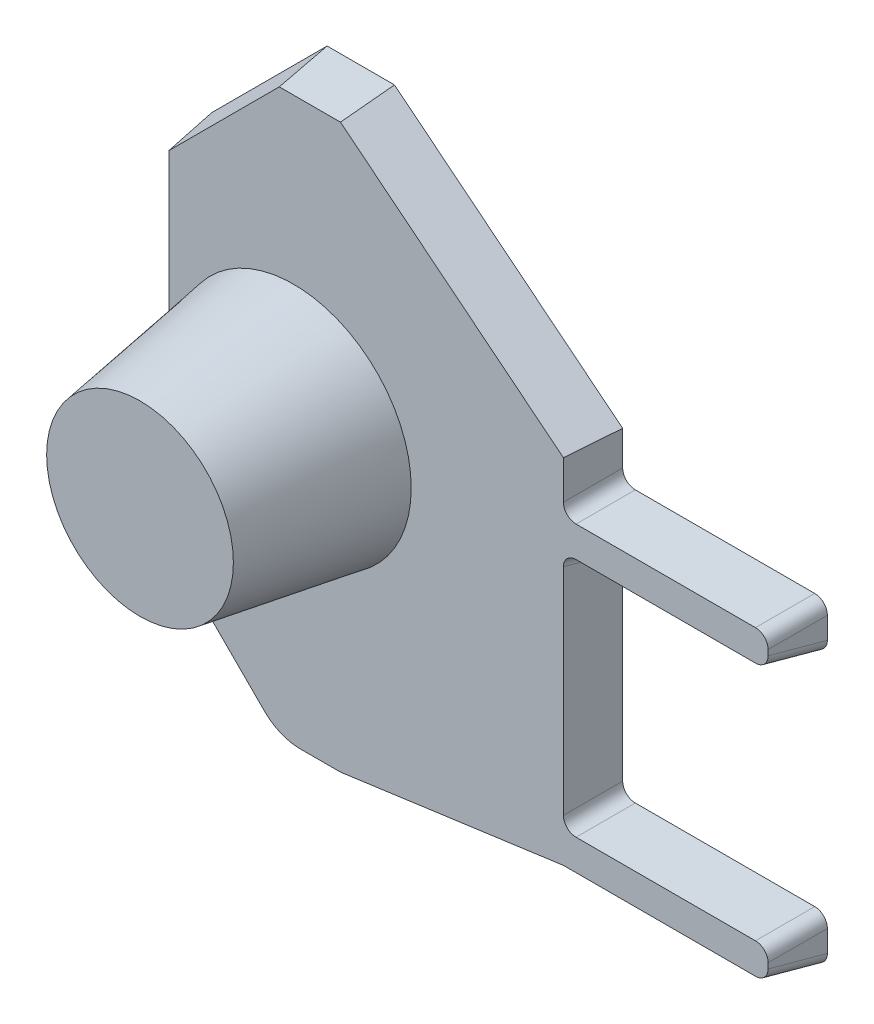
SolidWorks part; units mm, degrees
material "5052-H36"
ref_plane "Plano frontal" through (0, 0, 0) normal (0, 0, 1) x (1, 0, 0)
ref_plane "Plano superior" through (0, 0, 0) normal (0, 1, 0) x (1, 0, 0)
ref_plane "Plano direito" through (0, 0, 0) normal (1, 0, 0) x (0, 0, -1)
sketch "Esboço1" plane through (0, 0, 0) normal (0, 0, 1) x (1, 0, 0)
  line L0 (79.1281, 0) -> (0, 0) construction
  line L3 (4.9801, 55) -> (32.742, 55) construction
  line L6 (32.742, 55) -> (-22.7817, 55) construction
  line L12 (-22.7817, 55) -> (-44.3754, 33.4063)
  line L14 (-44.3754, -33.4063) -> (-22.7817, -55)
  line L15 (-22.7817, -55) -> (32.742, -55) construction
  line L18 (393.8557, 316.0739) -> (396.402, 318.6203) [skipped]
  line L19 (55, 501.996) -> (55, 520.8093) [skipped]
  line L20 (-316.0739, 393.8557) -> (-318.6203, 396.402) [skipped]
  line L21 (32.742, 55) -> (32.742, 20) construction
  line L22 (32.742, -49) -> (32.742, -55) construction
  line L23 (32.742, -49) -> (72.742, -49)
  line L25 (32.742, -43) -> (72.742, -43)
  line L26 (72.742, -49) -> (72.742, -43)
  line L27 (32.742, 4) -> (32.742, -43)
  line L28 (32.742, 4) -> (72.742, 4)
  line L30 (32.742, 10) -> (72.742, 10)
  line L31 (72.742, 4) -> (72.742, 10)
  line L32 (-44.3754, 33.4063) -> (-44.3754, -33.4063)
  line L33 (32.742, 55) -> (-10.8258, 55) construction
  line L34 (-55, 7.7563) -> (-55, -6.3461) [skipped]
  line L35 (-10.8258, 55) -> (32.742, 20)
  line L36 (32.742, 20) -> (32.742, 55) construction
  line L37 (32.742, 20) -> (32.742, 10)
  line L38 (-22.7817, 55) -> (-10.8258, 55)
  line L39 (-10.8258, -55) -> (32.742, -49)
  line L40 (32.742, -49) -> (32.742, -55) construction
  line L41 (32.742, -55) -> (-10.8258, -55) construction
  line L42 (-22.7817, -55) -> (-10.8258, -55)
  circle A0 centre (0, 0) radius 15 construction
  arc A3 (4.9801, 55) -> (0, -55.225) centre (0, 0) ccw construction
  point P14 (4.9801, 55)
  dimension "D1" = 30
  dimension "D2" = 35
  dimension "D5" = 110
  dimension "D3" = 43.5679
  dimension "D4" = 10
  dimension "D6" = 40
  dimension "D7" = 6
  dimension "D8" = 6
  dimension "D9" = 45
  dimension "D10" = 43.5679
  dimension "D11" = 6
extrude "Ressalto-extrusão1" add sketch "Esboço1" against normal blind 10 draft 9 draft outward yes
sketch "Esboço2" plane through (0, 0, 0) normal (0, 0, -1) x (-1, 0, 0)
  circle A1 centre (20, 0) radius 23
  dimension "D1" = 46
  dimension "D2" = 20
extrude "Ressalto-extrusão2" add sketch "Esboço2" against normal blind 30 draft 9
fillet "Filete1" radius 10 1 edges at (-23.1098, -55.7919, -5)
fillet "Filete2" radius 2.5 7 edges at (33.534, -42.2081, -5) (33.534, 10.7919, -5) (33.534, 3.2081, -5) (73.534, 3.2081, -5) (73.534, 10.7919, -5) (73.534, -49.7919, -5) (73.534, -42.2081, -5)
scale "Escala1" bodies to scale 103 scale about centroid uniform scaling yes scale factor 1.05
sketch "Esboço3" plane through (0, 0, -10.5634) normal (0, 0, -1) x (-1, 0, 0)
  line L0 (10, 25) -> (10, -25) construction
  circle A0 centre (10, 25) radius 2.5
  circle A1 centre (10, -25) radius 2.5
  point P0 (10, 0)
  dimension "D2" = 5
  dimension "D1" = 10
  dimension "D3" = 25
extrude "Corte-extrusão1" cut sketch "Esboço3" against normal blind 5
move or copy body "Corpo-Converter em corpo de malha1" [suppressed] bodies to move or copy 109 copy no translate (0, 0, 0) parameters "D1"=0, "D2"=0, "D3"=0
